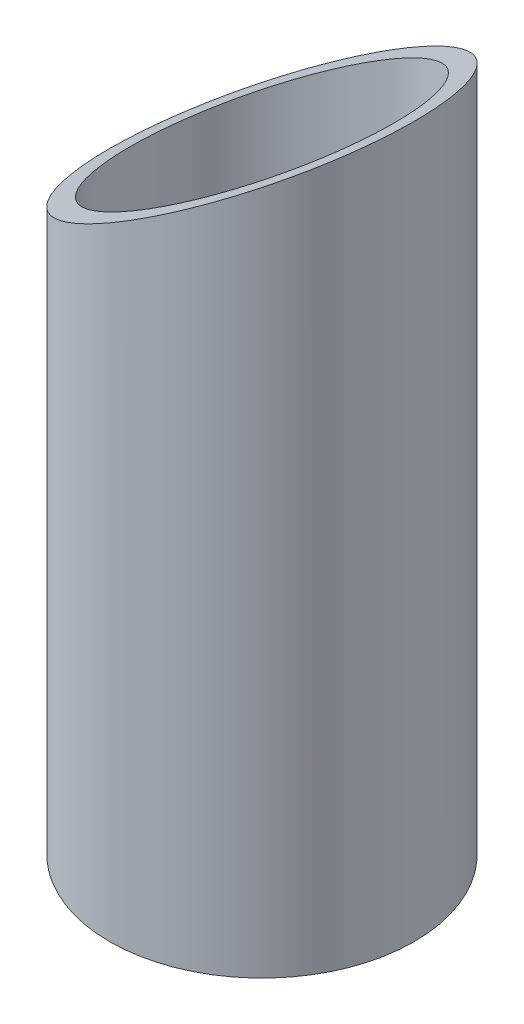
SolidWorks part; units mm, degrees
ref_plane "Front Plane" through (0, 0, 0) normal (0, 0, 1) x (1, 0, 0)
ref_plane "Top Plane" through (0, 0, 0) normal (0, 1, 0) x (1, 0, 0)
ref_plane "Right Plane" through (0, 0, 0) normal (1, 0, 0) x (0, 0, -1)
sketch "Sketch1" plane through (0, 0, 0) normal (0, 1, 0) x (1, 0, 0)
  circle A0 centre (0, 0) radius 15
  circle A1 centre (0, 0) radius 13
  point P4 (0, 0)
  dimension "D1" = 2
  dimension "D2" = 30
extrude "Boss-Extrude1" add sketch "Sketch1" along normal blind 70
sketch "Sketch2" plane through (0, 0, 0) normal (0, 0, 1) x (1, 0, 0)
  line L0 (15, 70) -> (-15, 70) construction
  line L1 (15, 70) -> (-15, 70)
  line L2 (15, 70) -> (-15, 52.6795)
  line L3 (-15, 70) -> (-15, 0) construction
  line L4 (-15, 52.6795) -> (-15, 70)
  dimension "D1" = 30
extrude "Cut-Extrude1" cut sketch "Sketch2" against normal through all both and the other way through all
sketch "Sketch5" plane through (0, 0, 0) normal (0, 0, 1) x (1, 0, 0)
  line L0 (0, 0) -> (40.4145, 0) construction
  line L1 (40.4145, 0) -> (0, 70) construction
  line L2 (0, 70) -> (0, 0) construction
  line L3 (15, 70) -> (55.4145, 0) construction
  point P6 (0, 0)
  point P7 (0, 0)
  dimension "D1" = 70
  dimension "D2" = 60
sketch "Sketch7" plane through (0, 0, 0) normal (1, 0, 0) x (0, 0, -1)
  line L0 (0, 70) -> (0, 0) construction
  line L1 (0, 70) -> (0, 0)
  line L2 (0, 0) -> (-24.5361, 0) construction
sketch "Sketch8" plane through (0, 0, 0) normal (0, 0, 1) x (1, 0, 0)
  point P0 (0, 0)
ref_plane "Plane1" through (15, 0, 0) normal (1, 0, 0) x (0, 0, -1)
sketch "Sketch9" plane through (15, 0, 0) normal (1, 0, 0) x (0, 0, -1)
  line L0 (0, 70) -> (15.3091, 70) construction
ref_plane "Plane2" through (41.5609, 23.9952, 0) normal (0.866, 0.5, 0) x (0, 0, -1)
